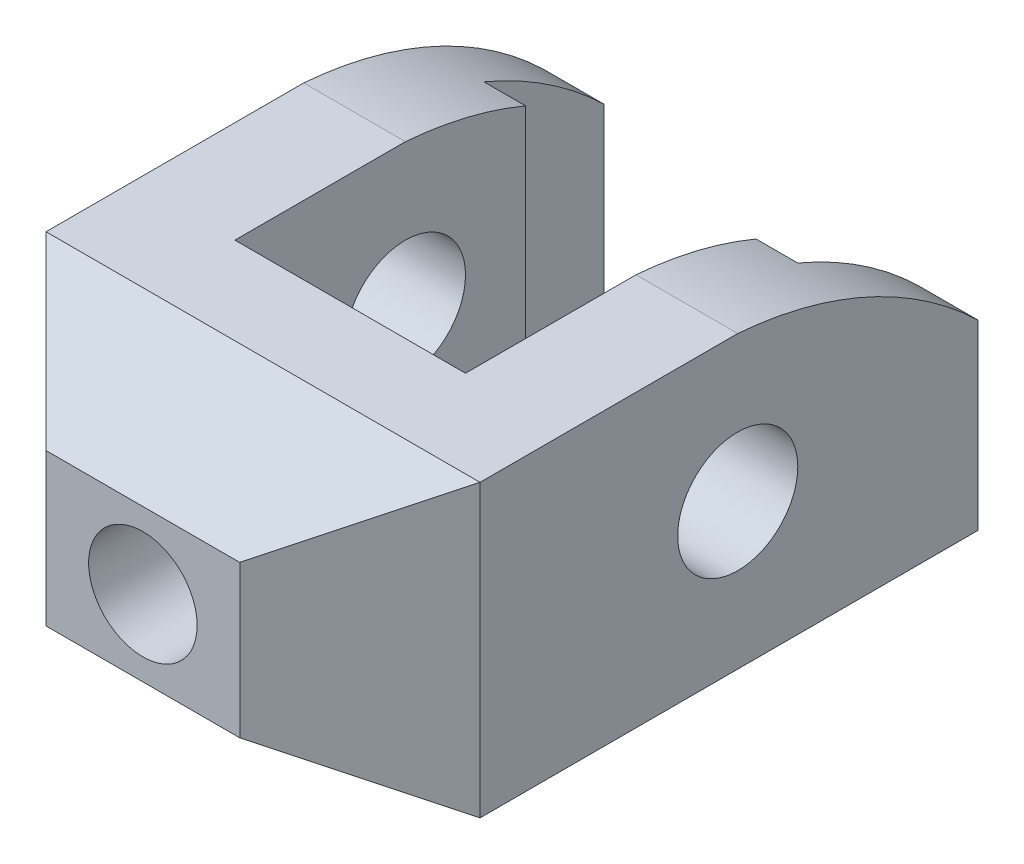
SolidWorks part; units mm, degrees
ref_plane "Front Plane" through (0, 0, 0) normal (0, 0, 1) x (1, 0, 0)
ref_plane "Top Plane" through (0, 0, 0) normal (0, 1, 0) x (1, 0, 0)
ref_plane "Right Plane" through (0, 0, 0) normal (1, 0, 0) x (0, 0, -1)
sketch "Sketch1" plane through (0, 0, 0) normal (0, 1, 0) x (1, 0, 0)
  line L0 (59.5, 0) -> (-59.5, 0)
  line L1 (-59.5, 0) -> (-59.5, 150)
  line L2 (-59.5, 150) -> (-81, 150)
  line L3 (-81, 150) -> (-81, 212)
  line L4 (-81, 212) -> (-112, 212)
  line L5 (-112, 212) -> (-112, -45)
  line L6 (-112, -45) -> (-50, -107)
  line L7 (-50, -107) -> (50, -107)
  line L8 (50, -107) -> (112, -45)
  line L9 (112, -45) -> (112, 212)
  line L10 (112, 212) -> (81, 212)
  line L11 (81, 212) -> (81, 150)
  line L12 (81, 150) -> (59.5, 150)
  line L13 (59.5, 150) -> (59.5, 0)
  point P4 (0, 0)
  dimension "D1" = 319
  dimension "D2" = 119
  dimension "D3" = 224
  dimension "D4" = 162
  dimension "D5" = 212
  dimension "D6" = 45
  dimension "D7" = 62
  dimension "D8" = 62
extrude "Boss-Extrude1" add sketch "Sketch1" along normal blind 150
sketch "Sketch3" plane through (0, 0, 0) normal (1, 0, 0) x (0, 0, -1)
  line L0 (-107, 150) -> (-107, 114.2043)
  line L1 (-107, 0) -> (-45, 0)
  line L3 (-45, 150) -> (-107, 150)
  line L4 (-45, 150) -> (-107, 114.2043)
  line L5 (-45, 0) -> (-107, 35.7957)
  line L6 (-107, 35.7957) -> (-107, 0)
  dimension "D1" = 30
extrude "Cut-Extrude1" cut sketch "Sketch3" against normal blind 112 and the other way blind 112
sketch "Sketch4" plane through (0, 0, 0) normal (1, 0, 0) x (0, 0, -1)
  line L0 (212, 150) -> (88, 150)
  line L1 (-45, 150) -> (212, 150) construction
  line L6 (212, 94) -> (212, 150)
  arc A0 (212, 94) -> (88, 150) centre (72.5911, -49.4055) ccw
  dimension "D1" = 200
  dimension "D2" = 124
  dimension "D3" = 56
extrude "Cut-Extrude2" cut sketch "Sketch4" against normal blind 112 and the other way blind 112
sketch "Sketch5" plane through (0, 0, 107) normal (0, 0, 1) x (1, 0, 0)
  line L0 (-112, 150) -> (-112, 0) construction
  line L1 (112, 0) -> (-112, 0) construction
  circle A0 centre (0, 75) radius 28
  dimension "D1" = 56
  dimension "D2" = 112
  dimension "D3" = 75
extrude "Cut-Extrude3" cut sketch "Sketch5" against normal blind 50
sketch "Sketch6" plane through (112, 0, 0) normal (1, 0, 0) x (0, 0, -1)
  line L0 (-45, 0) -> (212, 0) construction
  line L1 (212, 94) -> (212, 0) construction
  circle A0 centre (88, 75) radius 31
  dimension "D1" = 62
  dimension "D2" = 75
  dimension "D3" = 124
extrude "Cut-Extrude4" cut sketch "Sketch6" against normal blind 224
